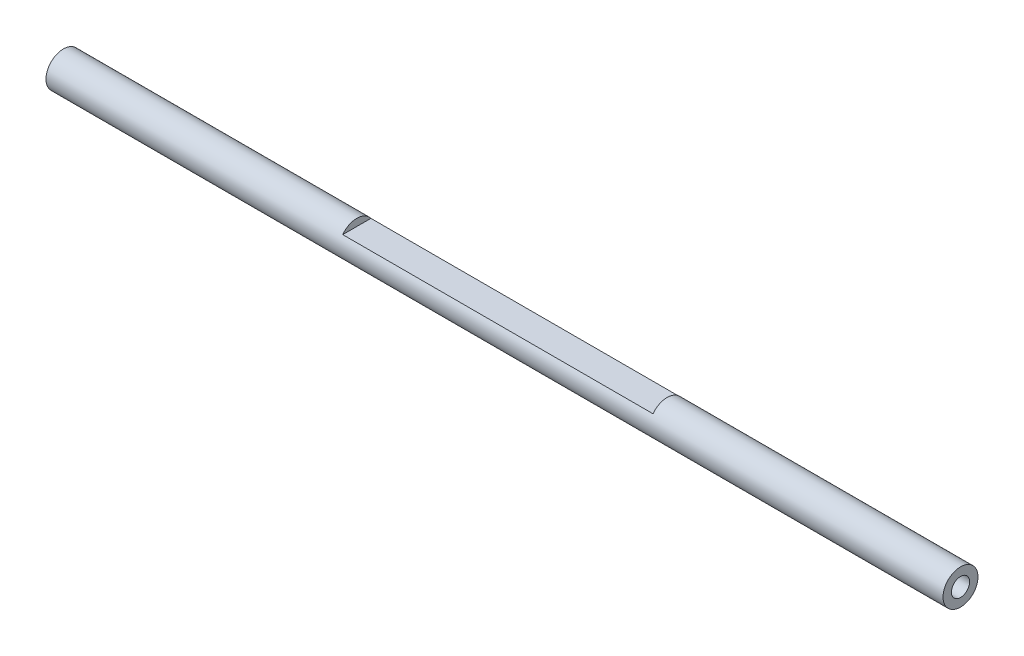
SolidWorks part; units mm, degrees
ref_plane "Front Plane" through (0, 0, 0) normal (0, 0, 1) x (1, 0, 0)
ref_plane "Top Plane" through (0, 0, 0) normal (0, 1, 0) x (1, 0, 0)
ref_plane "Right Plane" through (0, 0, 0) normal (1, 0, 0) x (0, 0, -1)
sketch "Sketch1" plane through (0, 0, 0) normal (1, 0, 0) x (0, 0, -1)
  line L1 (10, 8.45) -> (-10, 8.45)
  line L2 (10, 8.45) -> (10, -8.45)
  line L3 (10, -8.45) -> (-10, -8.45)
  line L4 (-10, 8.45) -> (-10, -8.45)
  line L5 (10, 8.45) -> (-10, -8.45) construction
  line L6 (10, -8.45) -> (-10, 8.45) construction
  circle A0 centre (0, 0) radius 8.45 construction
  point P0 (0, 0)
  dimension "D1" = 16.9
  dimension "D2" = 20
extrude "Boss-Extrude1" add sketch "Sketch1" along normal mid plane 47.5
sketch "Sketch2" plane through (23.75, 0, 0) normal (1, 0, 0) x (0, 0, -1)
  circle A0 centre (0, 0) radius 8.45
  dimension "D1" = 16.9
extrude "Boss-Extrude2" add sketch "Sketch2" along normal blind 193.05
hole_wizard "M10x1.25 Tapped Hole1" positions "3DSketch1" profile "Sketch3" tap size "M10x1.25" standard "DIN"
sketch3d "3DSketch1"
  point P0 (216.8, 0, 0)
sketch "Sketch3" plane through (216.8, 0, 0) normal (0, 1, 0) x (0, 0, -1)
  line L0 (0, 0) -> (0, 32.6438)
  line L1 (0, 32.6438) -> (4.4, 30)
  line L2 (4.4, 30) -> (4.4, 0)
  line L5 (4.4, 0) -> (0, 0)
  line L10 (0, 32.6438) -> (-4.4, 30) construction
  line L11 (0, -6.35) -> (0, 107.95) construction
  dimension "Tap Drill Dia." = 8.8
  dimension "Tap Drill Depth" = 30
  dimension "Drill Angle" = 118
mirror "Mirror1" about plane through (0, 0, 0) normal (1, 0, 0) of "M10x1.25 Tapped Hole1", "Boss-Extrude2"
sketch "Sketch5" plane through (0, 0, 0) normal (0, 1, 0) x (1, 0, 0)
  line L0 (0, 94.6683) -> (0, -76.9789) construction
  line L1 (-216.8, 8.45) -> (-216.8, -8.45) construction
  point P0 (-210.55, 0)
  point P6 (210.55, 0)
  dimension "D1" = 6.25
sketch "Sketch6" plane through (0, 0, 0) normal (1, 0, 0) x (0, 0, -1)
  circle A0 centre (0, 0) radius 8.45
  dimension "D1" = 16.9
extrude "Cut-Extrude-Thin1" cut sketch "Sketch6" against normal mid plane 60 thin
sketch "Sketch7" plane through (0, 0, 0) normal (0, 1, 0) x (1, 0, 0)
  line L1 (75, 20) -> (-75, 20)
  line L2 (75, 20) -> (75, -20)
  line L3 (75, -20) -> (-75, -20)
  line L4 (-75, 20) -> (-75, -20)
  line L5 (75, 20) -> (-75, -20) construction
  line L6 (75, -20) -> (-75, 20) construction
  point P0 (0, 0)
  dimension "D1" = 150
  dimension "D2" = 40
extrude "Cut-Extrude1" cut sketch "Sketch7" along normal blind 10 from offset 5
sketch3d "3DSketch2"
  line L0 (-210.55, 0, 0) -> (210.55, 0, 0) construction
sketch3d "3DSketch3"
  point P1 (0, 0, 0)
